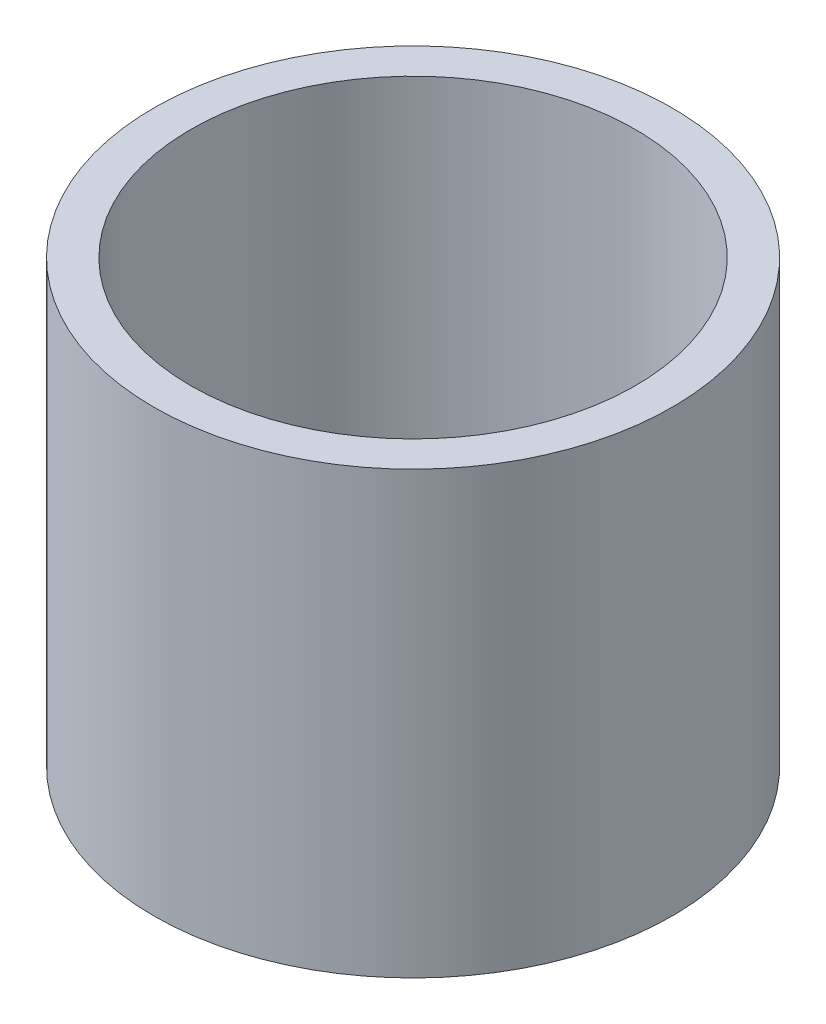
SolidWorks part; units mm, degrees
material "PVC 경질"
ref_plane "정면" through (0, 0, 0) normal (0, 0, 1) x (1, 0, 0)
ref_plane "윗면" through (0, 0, 0) normal (0, 1, 0) x (1, 0, 0)
ref_plane "우측면" through (0, 0, 0) normal (1, 0, 0) x (0, 0, -1)
other "질량 중심(COM)"
sketch "스케치1" plane through (0, 0, 0) normal (0, 1, 0) x (1, 0, 0)
  circle A0 centre (0, 0) radius 35
  dimension "D1" = 70
extrude "보스-돌출1" add sketch "스케치1" along normal blind 59.5
ref_plane "평면1" through (0, 5, 0) normal (0, 1, 0) x (1, 0, 0)
sketch "스케치2" plane through (0, 5, 0) normal (0, 1, 0) x (1, 0, 0)
  circle A0 centre (0, 0) radius 30
  dimension "D1" = 60
extrude "컷-돌출1" cut sketch "스케치2" along normal blind 59
